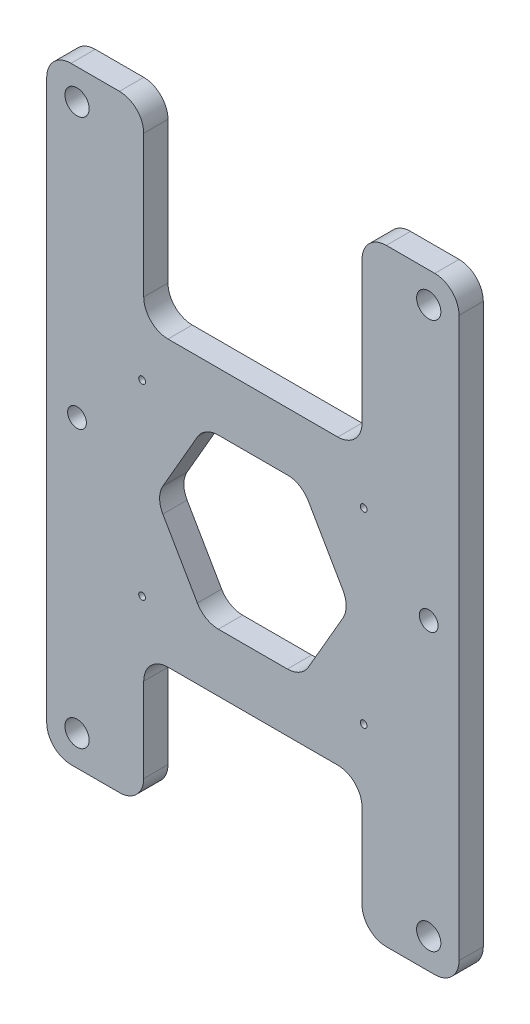
SolidWorks part; units mm, degrees
ref_plane "Front Plane" through (0, 0, 0) normal (0, 0, 1) x (1, 0, 0)
ref_plane "Top Plane" through (0, 0, 0) normal (0, 1, 0) x (1, 0, 0)
ref_plane "Right Plane" through (0, 0, 0) normal (1, 0, 0) x (0, 0, -1)
sketch "Sketch1" plane through (0, 0, 0) normal (0, 0, 1) x (1, 0, 0)
  line L0 (-29, -32) -> (29, -32) construction
  line L1 (-29, -32) -> (-29, 17) construction
  line L2 (29, -32) -> (29, 17) construction
  line L3 (-29, 17) -> (29, 17) construction
  line L4 (29, -32) -> (-29, 17) construction
  line L5 (-29, -32) -> (29, 17) construction
  line L6 (-53.975, -79.5094) -> (53.975, -79.5094) construction
  line L7 (-53.975, -79.5094) -> (-53.975, 79.5094)
  line L8 (53.975, -79.5094) -> (53.975, 79.5094)
  line L9 (-53.975, 79.5094) -> (53.975, 79.5094) construction
  line L10 (-53.975, -79.5094) -> (53.975, 79.5094) construction
  line L11 (53.975, -79.5094) -> (-53.975, 79.5094) construction
  line L12 (-28.575, 29.7) -> (28.575, 29.7)
  line L13 (-3.975, 0) -> (-53.975, 0) construction
  line L14 (-3.975, 0) -> (53.975, 0) construction
  line L15 (-53.975, 68) -> (53.975, 68) construction
  line L18 (-53.975, -68) -> (53.975, -68) construction
  line L21 (0, 68) -> (0, -68) construction
  line L22 (-53.975, 79.5094) -> (-28.575, 79.5094)
  line L23 (-28.575, 79.5094) -> (-28.575, 29.7)
  line L24 (53.975, 79.5094) -> (28.575, 79.5094)
  line L25 (28.575, 79.5094) -> (28.575, 29.7)
  line L26 (-28.575, -44.7) -> (-28.575, -79.5094)
  line L27 (-28.575, -79.5094) -> (-53.975, -79.5094)
  line L28 (-28.575, -44.7) -> (28.575, -44.7)
  line L29 (28.575, -44.7) -> (28.575, -79.5094)
  line L30 (28.575, -79.5094) -> (53.975, -79.5094)
  line L31 (32.5, -35.5) -> (-32.5, -35.5) construction
  line L32 (32.5, -35.5) -> (32.5, 20.5) construction
  line L33 (-32.5, -35.5) -> (-32.5, 20.5) construction
  line L34 (32.5, 20.5) -> (-32.5, 20.5) construction
  line L35 (32.5, -35.5) -> (-32.5, 20.5) construction
  line L36 (-32.5, -35.5) -> (32.5, 20.5) construction
  line L38 (-12.7, -29.497) -> (12.7, -29.497)
  line L39 (12.7, -29.497) -> (25.4, -7.5)
  line L40 (25.4, -7.5) -> (12.7, 14.497)
  line L41 (12.7, 14.497) -> (-12.7, 14.497)
  line L42 (-12.7, 14.497) -> (-25.4, -7.5)
  line L43 (-25.4, -7.5) -> (-12.7, -29.497)
  circle A0 centre (29, 17) radius 0.889
  circle A1 centre (29, -32) radius 0.889
  circle A2 centre (-29, -32) radius 0.889
  circle A3 centre (-29, 17) radius 0.889
  circle A10 centre (-46.0375, 71.5719) radius 3.175
  circle A11 centre (46.0375, 71.5719) radius 3.175
  circle A12 centre (-46.0375, -71.5719) radius 3.175
  circle A13 centre (46.0375, -71.5719) radius 3.175
  circle A14 centre (0, -7.5) radius 21.997 construction
  circle A15 centre (-46.0375, 0) radius 2.4574
  circle A16 centre (46.0375, 0) radius 2.4574
  point P1 (0, 0)
  point P2 (0, 0)
  point P28 (0, -7.5)
  point P35 (0, 29.7)
  point P43 (0, -7.5)
  dimension "D1" = 1.778
  dimension "D7" = 3.5719
  dimension "D9" = 7.9375
  dimension "D12" = 6.35
  dimension "D19" = 4.9149
  dimension "D2" = 58
  dimension "D3" = 49
  dimension "D4" = 136
  dimension "D5" = 107.95
  dimension "D6" = 25.4
  dimension "D8" = 7.9375
  dimension "D10" = 36
  dimension "D11" = 3.5719
  dimension "D13" = 12.7
  dimension "D14" = 12.7
  dimension "D15" = 65
  dimension "D16" = 56
  dimension "D17" = 25.4
  dimension "D18" = 25.4
extrude "Boss-Extrude1" add sketch "Sketch1" along normal blind 6.35
fillet "Fillet3" radius 6.35 18 edges at (-12.7, -29.497, 3.175) (12.7, -29.497, 3.175) (-25.4, -7.5, 3.175) (25.4, -7.5, 3.175) (12.7, 14.497, 3.175) (-12.7, 14.497, 3.175) (-53.975, -79.5094, 3.175) (28.575, -44.7, 3.175) (-28.575, -44.7, 3.175) (-28.575, -79.5094, 3.175) (28.575, -79.5094, 3.175) (53.975, -79.5094, 3.175) (53.975, 79.5094, 3.175) (-28.575, 79.5094, 3.175) (-53.975, 79.5094, 3.175) (28.575, 79.5094, 3.175) (28.575, 29.7, 3.175) (-28.575, 29.7, 3.175)
